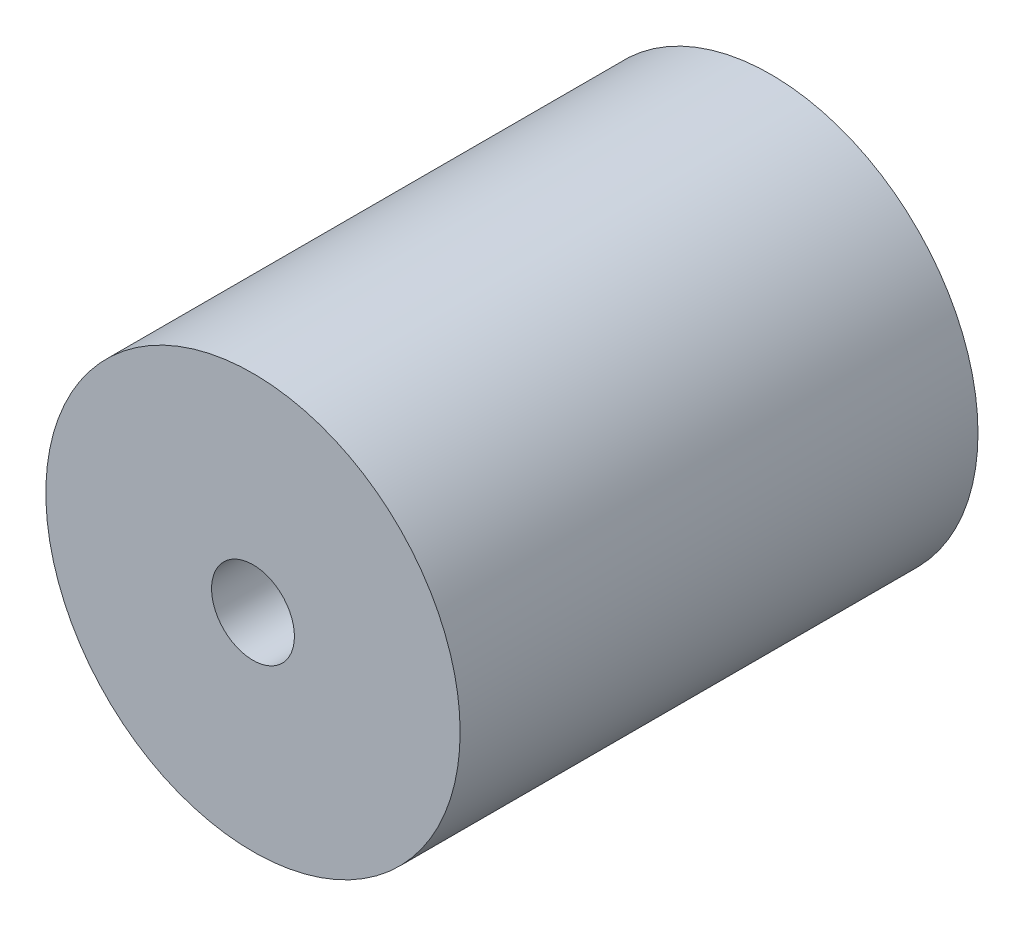
SolidWorks part; units mm, degrees
ref_plane "Front Plane" through (0, 0, 0) normal (0, 0, 1) x (1, 0, 0)
ref_plane "Top Plane" through (0, 0, 0) normal (0, 1, 0) x (1, 0, 0)
ref_plane "Right Plane" through (0, 0, 0) normal (1, 0, 0) x (0, 0, -1)
sketch "Sketch1" plane through (0, 0, 0) normal (0, 0, 1) x (1, 0, 0)
  circle A0 centre (0, 0) radius 10
extrude "Body" add sketch "Sketch1" along normal blind 25
sketch "Sketch2" plane through (0, 0, 0) normal (0, 0, 1) x (1, 0, 0)
  circle A0 centre (0, 0) radius 4
extrude "Bore_low" cut sketch "Sketch2" along normal blind 12
ref_plane "Plane_z15" through (0, 0, 15) normal (0, 0, 1) x (1, 0, 0)
sketch "Sketch3" plane through (0, 0, 15) normal (0, 0, 1) x (1, 0, 0)
  circle A0 centre (0, 0) radius 2
extrude "Bore_high" cut sketch "Sketch3" along normal blind 10
